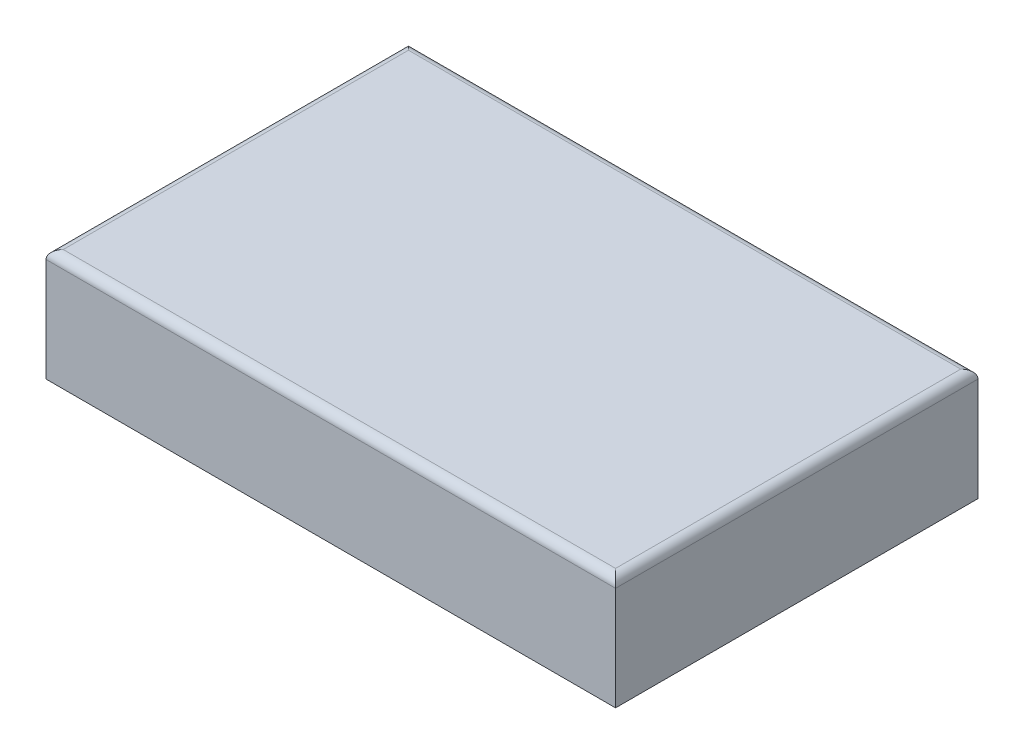
SolidWorks part; units mm, degrees
material "ABS"
ref_plane "Front Plane" through (0, 0, 0) normal (0, 0, 1) x (1, 0, 0)
ref_plane "Top Plane" through (0, 0, 0) normal (0, 1, 0) x (1, 0, 0)
ref_plane "Right Plane" through (0, 0, 0) normal (1, 0, 0) x (0, 0, -1)
sketch "Sketch1" plane through (0, 0, 0) normal (0, 1, 0) x (1, 0, 0)
  line L1 (-33, 21) -> (33, 21)
  line L2 (-33, 21) -> (-33, -21)
  line L3 (-33, -21) -> (33, -21)
  line L4 (33, 21) -> (33, -21)
  line L5 (-33, 21) -> (33, -21) construction
  line L6 (-33, -21) -> (33, 21) construction
  line L7 (-30, 18) -> (30, 18)
  line L8 (-30, 18) -> (-30, -18)
  line L9 (-30, -18) -> (30, -18)
  line L10 (30, 18) -> (30, -18)
  line L11 (-30, 18) -> (30, -18) construction
  line L12 (-30, -18) -> (30, 18) construction
  point P0 (0, 0)
  point P6 (0, 0)
  dimension "D1" = 36
  dimension "D2" = 60
  dimension "D3" = 3
  dimension "D4" = 3
extrude "Boss-Extrude1" add sketch "Sketch1" along normal blind 10
sketch "Sketch2" plane through (0, 0, 0) normal (0, -1, 0) x (1, 0, 0)
  line L1 (-33, 21) -> (33, 21)
  line L2 (-33, 21) -> (-33, -21)
  line L3 (-33, -21) -> (33, -21)
  line L4 (33, 21) -> (33, -21)
sketch "Sketch3" plane through (0, 10, 0) normal (0, 1, 0) x (1, 0, 0)
  line L1 (-33, 21) -> (33, 21)
  line L2 (-33, 21) -> (-33, -21)
  line L3 (-33, -21) -> (33, -21)
  line L4 (33, 21) -> (33, -21)
extrude "Boss-Extrude3" add sketch "Sketch3" along normal blind 3
fillet "Fillet2" radius 1 4 edges at (0, 13, -21) (33, 13, 0) (0, 13, 21) (-33, 13, 0)
